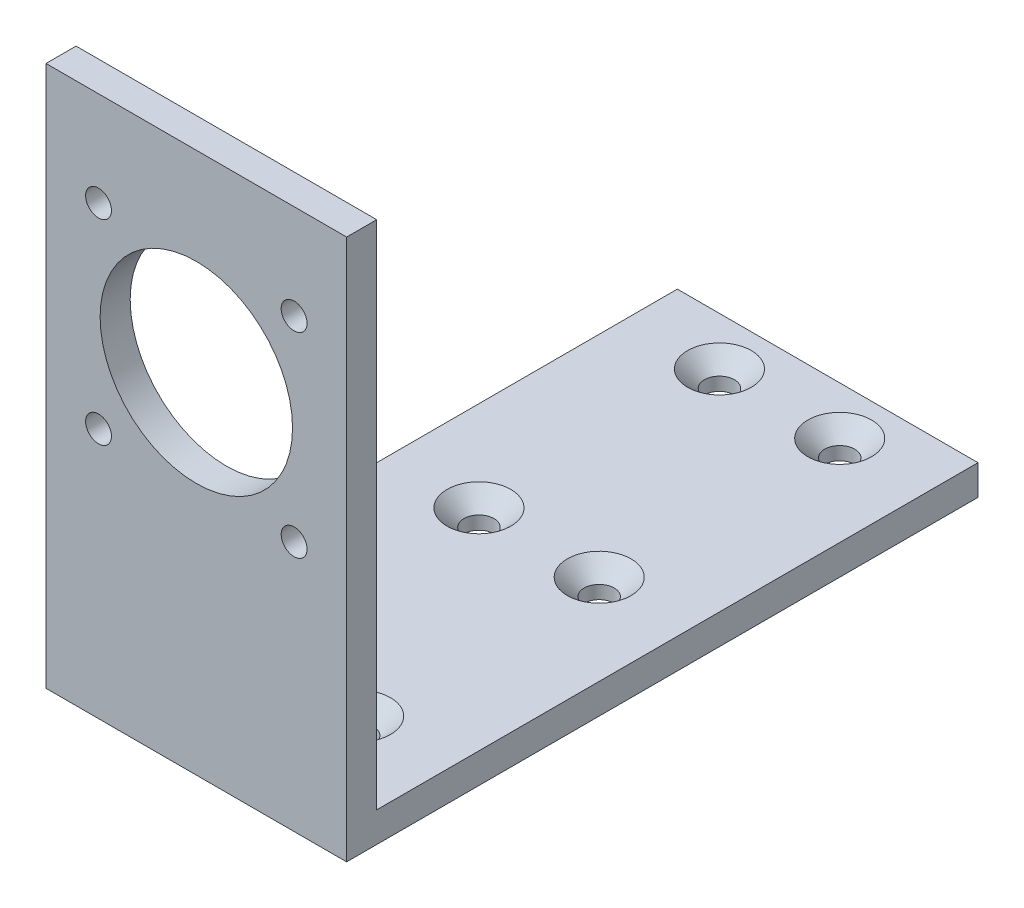
SolidWorks part; units mm, degrees
ref_plane "Front Plane" through (0, 0, 0) normal (0, 0, 1) x (1, 0, 0)
ref_plane "Top Plane" through (0, 0, 0) normal (0, 1, 0) x (1, 0, 0)
ref_plane "Right Plane" through (0, 0, 0) normal (1, 0, 0) x (0, 0, -1)
sketch "Sketch2" plane through (0, 0, 0) normal (0, 0, 1) x (1, 0, 0)
  line L0 (-25, 67) -> (25, 67) construction
  line L1 (-25, 45) -> (25, 45)
  line L2 (-25, 45) -> (-25, -45)
  line L3 (-25, -45) -> (25, -45)
  line L4 (25, 45) -> (25, -45)
  line L5 (0, 13) -> (0, 36.7952) construction
  line L6 (0, 13) -> (-16.2635, 29.2635) construction
  circle A0 centre (0, 13) radius 16
  circle A1 centre (-16.2635, 29.2635) radius 2.15
  circle A2 centre (16.2635, 29.2635) radius 2.15
  circle A3 centre (16.2635, -3.2635) radius 2.15
  circle A4 centre (-16.2635, -3.2635) radius 2.15
  point P0 (0, 0)
  point P22 (0, 13)
  dimension "D3" = 32
  dimension "D6" = 23
  dimension "D5" = 4.3
  dimension "D1" = 90
  dimension "D2" = 50
  dimension "D4" = 58
  dimension "D7" = 45
  dimension "D8" = 4
extrude "Boss-Extrude1" add sketch "Sketch2" along normal blind 5
sketch "Sketch3" plane through (0, 0, 0) normal (0, 0, -1) x (-1, 0, 0)
  line L0 (-25, -40) -> (25, -40)
  line L1 (-25, -45) -> (-25, 45) construction
  line L2 (25, 45) -> (25, -45) construction
  line L3 (25, -40) -> (25, -45)
  line L4 (25, -45) -> (-25, -45)
  line L5 (-25, -45) -> (-25, -40)
  dimension "D1" = 5
extrude "Boss-Extrude2" add sketch "Sketch3" along normal blind 100
sketch "Sketch4" plane through (0, -40, 0) normal (0, 1, 0) x (1, 0, 0)
  line L0 (-25, 100) -> (-25, 0) construction
  line L1 (25, 100) -> (25, 0) construction
  circle A0 centre (-10, 92.0023) radius 2.5
  circle A1 centre (10, 92.0023) radius 2.5
  circle A2 centre (-10, 12.0023) radius 2.5
  circle A3 centre (10, 12.0023) radius 2.5
  circle A4 centre (-10, 52.0023) radius 2.5
  circle A5 centre (10, 52.0023) radius 2.5
  dimension "D1" = 5
  dimension "D5" = 2
  dimension "D2" = 15
  dimension "D4" = 15
  dimension "D3" = 2
  dimension "D6" = 2
extrude "Cut-Extrude1" cut sketch "Sketch4" against normal through all
chamfer "Chamfer1" distance 2.8 angle 45 6 edges at (7.5, -40, -12.0023) (-12.5, -40, -12.0023) (-12.5, -40, -52.0023) (7.5, -40, -52.0023) (7.5, -40, -92.0023) (-12.5, -40, -92.0023)
